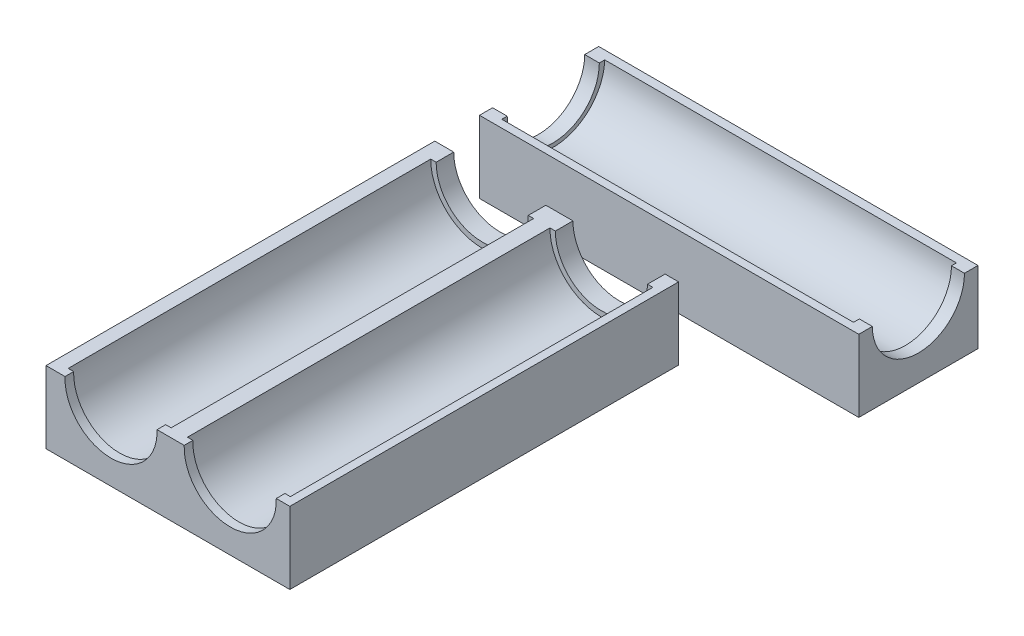
SolidWorks part; units mm, degrees
ref_plane "Plan de face" through (0, 0, 0) normal (0, 0, 1) x (1, 0, 0)
ref_plane "Plan de dessus" through (0, 0, 0) normal (0, 1, 0) x (1, 0, 0)
ref_plane "Plan de droite" through (0, 0, 0) normal (1, 0, 0) x (0, 0, -1)
sketch "Esquisse1" plane through (0, 0, 0) normal (0, 1, 0) x (1, 0, 0)
  line L0 (0, 0) -> (0, 102)
  line L1 (0, 102) -> (70, 102)
  line L2 (70, 102) -> (70, 80)
  line L3 (70, 80) -> (45, 80)
  line L4 (45, 80) -> (45, 0)
  line L5 (45, 0) -> (0, 0)
  dimension "D1" = 45
  dimension "D2" = 80
  dimension "D3" = 22
  dimension "D4" = 70
extrude "Boss.-Extru.1" add sketch "Esquisse1" along normal blind 13.3
sketch "Esquisse2" plane through (0, 0, 0) normal (0, 0, 1) x (1, 0, 0)
  circle A0 centre (12, 13) radius 8.5
  circle A1 centre (34, 13) radius 8.5
  point P4 (0, 0)
  dimension "D1" = 17
  dimension "D2" = 17
  dimension "D3" = 13
  dimension "D4" = 12
  dimension "D5" = 22
extrude "Enlèv. mat.-Extru.1" cut sketch "Esquisse2" against normal blind 68
sketch "Esquisse3" plane through (0, 0, -68) normal (0, 0, 1) x (1, 0, 0)
  line L0 (20.4947, 13.3) -> (3.5053, 13.3) construction
  line L1 (42.4947, 13.3) -> (25.5053, 13.3) construction
  circle A0 centre (12, 13.3) radius 9.5
  circle A1 centre (34, 13.3) radius 9.5
  dimension "D1" = 19
  dimension "D2" = 19
extrude "Enlèv. mat.-Extru.2" cut sketch "Esquisse3" along normal blind 66.4 and the other way blind 0.5
sketch "Esquisse5" plane through (45, 0, 0) normal (1, 0, 0) x (0, 0, -1)
  line L0 (71.7462, 13.3) -> (80, 13.3)
  line L1 (0, 13.3) -> (80, 13.3) construction
  line L2 (80, 13.3) -> (80, 0)
  line L3 (0, 0) -> (80, 0) construction
  line L4 (80, 0) -> (71.7462, 0)
  line L5 (71.7462, 0) -> (71.7462, 13.3)
  point P7 (90, 13.3)
extrude "Enlèv. mat.-Extru.3" cut sketch "Esquisse5" against normal through all
sketch "Esquisse7" plane through (0, 0, -68.5) normal (0, 0, 1) x (1, 0, 0)
  line L0 (43.5, 13.3) -> (24.5, 13.3) construction
  line L1 (21.5, 13.3) -> (2.5, 13.3) construction
  circle A0 centre (34, 13.3) radius 8.5
  circle A1 centre (12, 13.3) radius 8.5
  dimension "D1" = 17
extrude "Enlèv. mat.-Extru.5" cut sketch "Esquisse7" against normal blind 4
sketch "Esquisse6" plane through (70, 0, 0) normal (1, 0, 0) x (0, 0, -1)
  line L0 (80, 13.3) -> (102, 13.3) construction
  circle A0 centre (91.0033, 13.3) radius 8.5
  dimension "D1" = 17
extrude "Enlèv. mat.-Extru.4" cut sketch "Esquisse6" against normal blind 67.3
sketch "Esquisse8" plane through (2.7, 0, 0) normal (1, 0, 0) x (0, 0, -1)
  circle A0 centre (90.9155, 13.571) radius 9.5
  point P4 (97.2554, 13.3)
  dimension "D1" = 19
extrude "Enlèv. mat.-Extru.6" cut sketch "Esquisse8" along normal blind 64.9
sketch "Esquisse9" plane through (2.7, 0, 0) normal (1, 0, 0) x (0, 0, -1)
  line L0 (100.4117, 13.3) -> (81.4194, 13.3) construction
  circle A0 centre (90.9155, 13.3) radius 8.5
  point P4 (94.8777, 13.3)
  dimension "D1" = 17
extrude "Enlèv. mat.-Extru.7" cut sketch "Esquisse9" against normal blind 64.2
